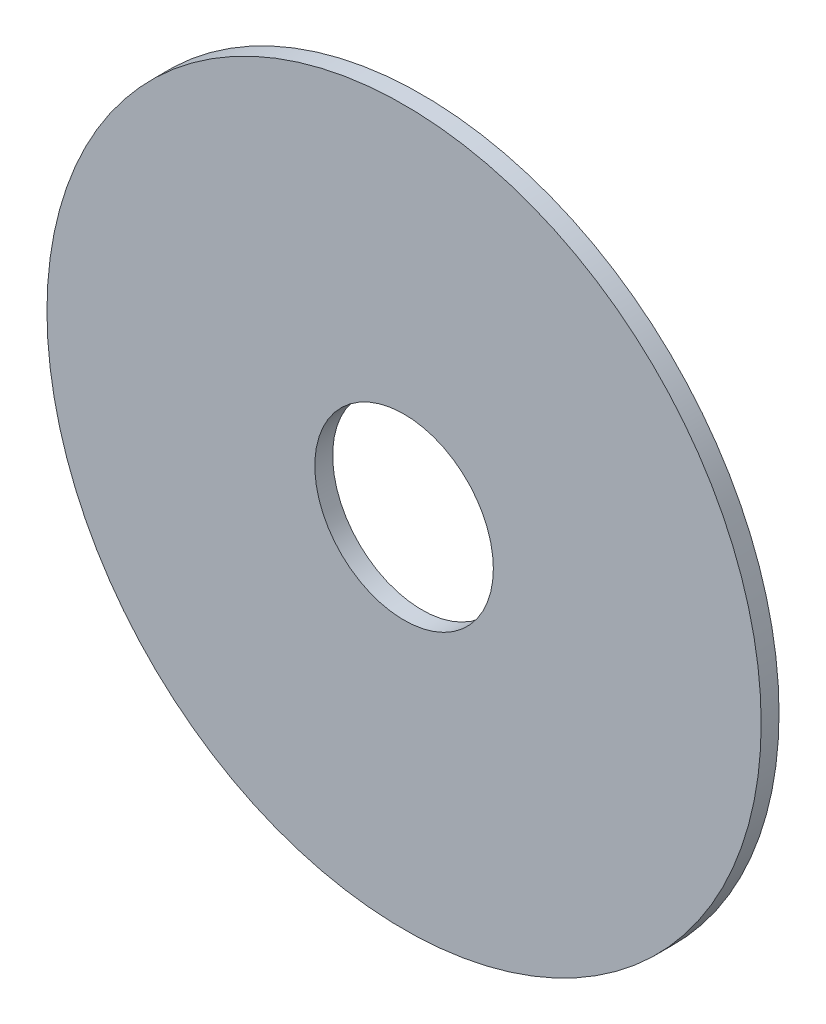
SolidWorks part; units mm, degrees
ref_plane "前视基准面" through (0, 0, 0) normal (0, 0, 1) x (1, 0, 0)
ref_plane "上视基准面" through (0, 0, 0) normal (0, 1, 0) x (1, 0, 0)
ref_plane "右视基准面" through (0, 0, 0) normal (1, 0, 0) x (0, 0, -1)
sketch "草图1" plane through (0, 0, 0) normal (0, 0, 1) x (1, 0, 0)
  circle A0 centre (0, 0) radius 25
  circle A1 centre (0, 0) radius 100
  dimension "D1" = 50
  dimension "D2" = 200
extrude "凸台-拉伸1" add sketch "草图1" along normal blind 5
